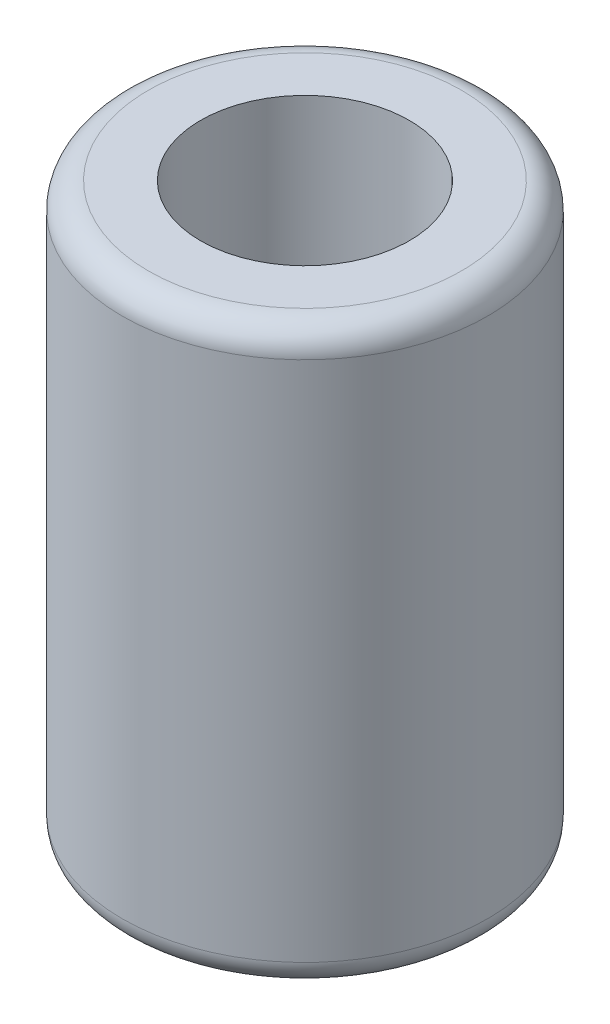
SolidWorks part; units mm, degrees
ref_plane "Front Plane" through (0, 0, 0) normal (0, 0, 1) x (1, 0, 0)
ref_plane "Top Plane" through (0, 0, 0) normal (0, 1, 0) x (1, 0, 0)
ref_plane "Right Plane" through (0, 0, 0) normal (1, 0, 0) x (0, 0, -1)
sketch "Sketch1" plane through (0, 0, 0) normal (0, 1, 0) x (1, 0, 0)
  circle A0 centre (0, 0) radius 7
  dimension "D1" = 14
extrude "Boss-Extrude1" add sketch "Sketch1" along normal blind 22
sketch "Sketch2" plane through (0, 22, 0) normal (0, 1, 0) x (1, 0, 0)
  circle A0 centre (0, 0) radius 4
  dimension "D1" = 8
extrude "Cut-Extrude1" cut sketch "Sketch2" against normal through all
fillet "Fillet1" radius 1 1 edges at (0, 22, 7)
fillet "Fillet2" radius 1 1 edges at (0, 0, 7)
